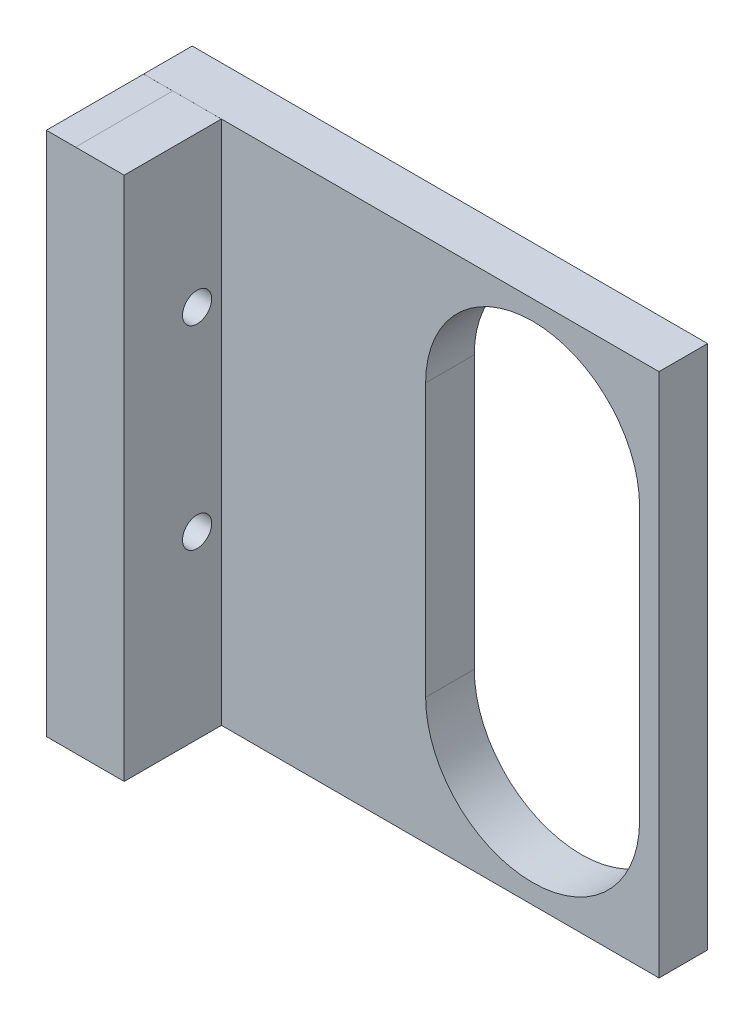
SolidWorks part; units mm, degrees
ref_plane "前视基准面" through (0, 0, 0) normal (0, 0, 1) x (1, 0, 0)
ref_plane "上视基准面" through (0, 0, 0) normal (0, 1, 0) x (1, 0, 0)
ref_plane "右视基准面" through (0, 0, 0) normal (1, 0, 0) x (0, 0, -1)
other "Configuration Table"
sketch "草图2" plane through (0, 0, 0) normal (0, 0, 1) x (1, 0, 0)
  line L0 (13, 4.25) -> (-40, 4.25)
  line L1 (-40, 4.25) -> (-40.0039, 58.25)
  line L2 (13, 4.25) -> (12.9961, 58.25)
  line L3 (-40.0039, 58.25) -> (12.9961, 58.25)
  dimension "D1" = 53
  dimension "D2" = 54
  dimension "D3" = 53
  dimension "D4" = 54
extrude "凸台-拉伸1" add sketch "草图2" along normal blind 5 contours L1 L3 L2 L0
sketch "草图3" plane through (0, 0, 0) normal (0, 0, 1) x (1, 0, 0)
  line L0 (-11, 17.25) -> (-11, 45.25)
  line L3 (11, 17.25) -> (11, 45.25)
  arc A2 (-11, 17.25) -> (11, 17.25) centre (0, 17.25) ccw
  arc A3 (-11, 45.25) -> (11, 45.25) centre (0, 45.25) cw
  point P5 (0, 17.25)
  point P7 (0, 17.25)
extrude "切除-拉伸11" cut sketch "草图3" along normal blind 5
sketch3d "3D草图1"
  point P0 (12.9892, 152.8253, 4.89)
sketch3d "3D草图2"
  point P0 (-25.1784, 27.3023, 5)
ref_plane "基准面1" through (0, 0, 5) normal (0, 0, 1) x (1, 0, 0)
sketch "草图4" plane through (0, 0, 5) normal (0, 0, 1) x (1, 0, 0)
  line L0 (-40, 4.25) -> (-37, 4.25)
  line L1 (-40.0039, 58.2474) -> (-37.0039, 58.2474)
  line L2 (-37.0039, 58.2474) -> (-37, 4.25)
  line L3 (-40.0039, 58.2474) -> (-40, 4.25)
extrude "凸台-拉伸2" add sketch "草图4" along normal blind 10
sketch3d "3D草图3"
  point P0 (-40.0027, 40.8021, 11.1914)
ref_plane "基准面2" through (-39.9997, -0.0029, 0) normal (-1, -0.0001, 0) x (0, 0, 1)
sketch "草图5" plane through (-39.9997, -0.0029, 0) normal (-1, -0.0001, 0) x (0, 0, 1)
  circle A0 centre (7.5, 42.7503) radius 1.5
  circle A1 centre (7.5, 22.7503) radius 1.5
extrude "切除-拉伸12" cut sketch "草图5" against normal up to next
sketch "草图6" plane through (-36.9997, -0.0027, 0) normal (1, 0.0001, 0) x (0, 0, -1)
  line L0 (-15, 58.2501) -> (-5, 58.2501)
  line L1 (-5, 58.2501) -> (-5, 4.2491)
  line L2 (-5, 4.2491) -> (-15, 4.2527)
  line L3 (-15, 4.2527) -> (-15, 58.2501)
extrude "凸台-拉伸3" add sketch "草图6" along normal blind 5
sketch "草图7" plane through (-31.9997, -0.0023, 0) normal (1, 0.0001, 0) x (0, 0, -1)
  circle A0 centre (-7.5, 42.7501) radius 1.5
  circle A1 centre (-7.5, 22.7501) radius 1.5
extrude "切除-拉伸13" cut sketch "草图7" against normal blind 5
